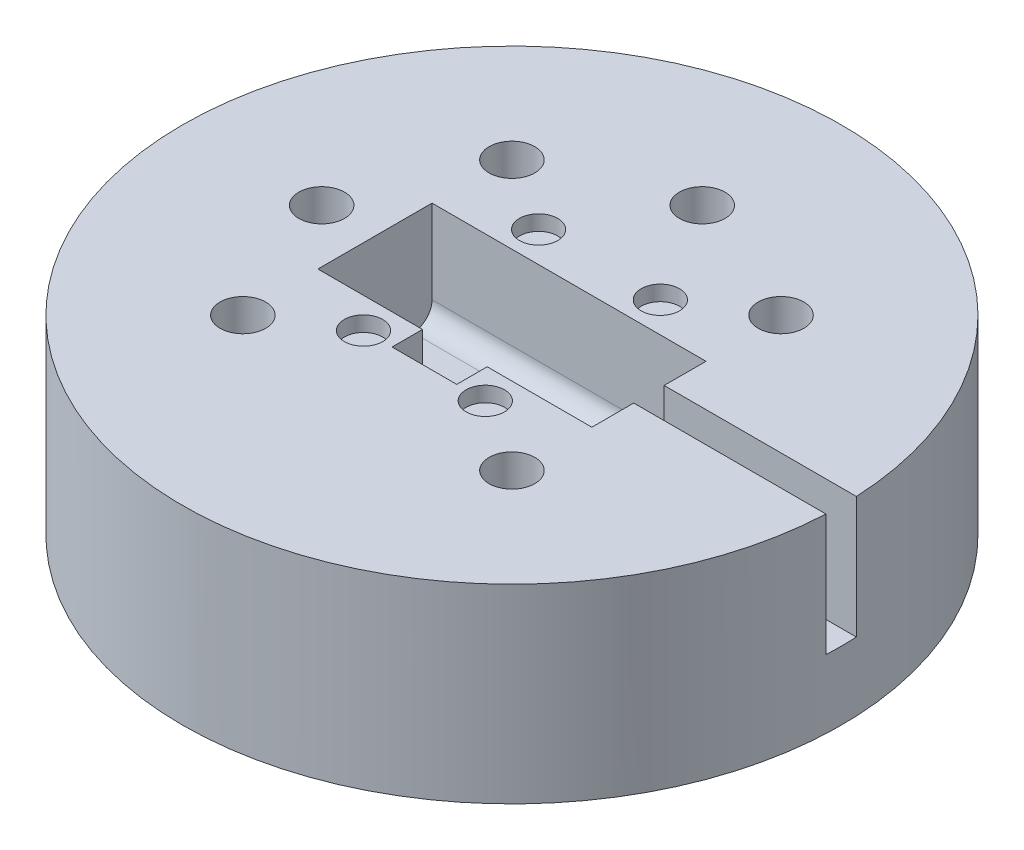
SolidWorks part; units mm, degrees
ref_plane "Front Plane" through (0, 0, 0) normal (0, 0, 1) x (1, 0, 0)
ref_plane "Top Plane" through (0, 0, 0) normal (0, 1, 0) x (1, 0, 0)
ref_plane "Right Plane" through (0, 0, 0) normal (1, 0, 0) x (0, 0, -1)
sketch "Sketch1" plane through (0, 0, 0) normal (0, 1, 0) x (1, 0, 0)
  circle A0 centre (0, 0) radius 50 construction
  circle A1 centre (0, 0) radius 86.6
extrude "Boss-Extrude1" add sketch "Sketch1" along normal blind 50
sketch "Sketch2" plane through (0, 50, 0) normal (0, 1, 0) x (1, 0, 0)
  circle A0 centre (0, 0) radius 50 construction
  circle A1 centre (0, 50) radius 6
  circle A2 centre (35.3553, 35.3553) radius 6
  circle A4 centre (35.3553, -35.3553) radius 6
  circle A6 centre (-35.3553, -35.3553) radius 6
  circle A7 centre (-50, 0) radius 6
  circle A8 centre (-35.3553, 35.3553) radius 6
  arc A9 (49.64, 5.9892) -> (49.64, -5.9892) centre (50, 0) ccw [skipped]
  arc A10 (5.9892, -49.64) -> (-5.9892, -49.64) centre (0, -50) ccw [skipped]
  point P21 (0, 0)
  dimension "D1" = 8
extrude "Cut-Extrude1" cut sketch "Sketch2" against normal blind 50
sketch "Sketch3" plane through (0, 50, 0) normal (0, 1, 0) x (1, 0, 0)
  line L0 (0, -15) -> (0, -23)
  line L1 (-36, -15) -> (36, -15)
  line L2 (-36, -15) -> (-36, 15)
  line L3 (-36, 15) -> (36, 15)
  line L4 (36, -15) -> (36, 15)
  line L5 (-36, -15) -> (36, 15) construction
  line L6 (-36, 15) -> (36, -15) construction
  line L7 (0, -23) -> (8.5, -23)
  line L8 (8.5, -23) -> (8.5, -15)
  line L9 (0, -23) -> (-8.5, -23)
  line L10 (-8.5, -23) -> (-8.5, -15)
  point P0 (0, 0)
  dimension "D1" = 8
  dimension "D2" = 8.5
  dimension "D3" = 72
  dimension "D4" = 30
extrude "Cut-Extrude2" cut sketch "Sketch3" against normal blind 27 contours L7 L8 L1 L0 | L10 L9 L0 L1 | L1 L4 L3 L2
fillet "Fillet1" radius 5 1 edges at (0, 23, -15)
fillet "Fillet2" radius 5 2 edges at (22.25, 23, 15) (-22.25, 23, 15)
sketch "Sketch4" plane through (0, 50, 0) normal (0, 1, 0) x (1, 0, 0)
  line L3 (18.5076, 4) -> (86.5076, 4)
  line L4 (18.5076, -4) -> (86.5076, -4)
  circle A1 centre (18.5076, 0) radius 4
  circle A2 centre (0, 0) radius 86.6 construction
  arc A3 (86.5076, 4) -> (86.5076, -4) centre (86.5076, 0) cw
  point P9 (20.1173, 0)
  line M8 (36, 15) -> (36, -15)
  circle M18 centre (0, 0) radius 86.6
  dimension "D1" = 8
  dimension "D2" = 68
extrude "Cut-Extrude3" cut sketch "Sketch4" against normal blind 32 contours L4 L3 M8 M18 | A1 L4 L3 M8 | A1 | A3 M18
sketch "Sketch5" plane through (0, 50, 0) normal (0, 1, 0) x (1, 0, 0)
  line L0 (-36, -15) -> (-36, -23) construction
  line L1 (-36, -23) -> (36, -23) construction
  line L2 (36, -23) -> (36, -15) construction
  line L3 (-36, -15) -> (36, -15) construction
  line L4 (-36, 15) -> (-36, 23) construction
  line L5 (-36, 23) -> (36, 23) construction
  line L6 (36, 23) -> (36, 15) construction
  line L7 (36, 15) -> (-36, 15) construction
  line L8 (-16, 23) -> (-16, 15) construction
  line L9 (16, 23) -> (16, 15) construction
  line L10 (-16, -15) -> (-16, -23) construction
  line L11 (16, -15) -> (16, -23) construction
  circle A0 centre (-16, -23) radius 5.043
  circle A1 centre (16, -23) radius 5.043
  circle A2 centre (16, 23) radius 5.043
  circle A3 centre (-16, 23) radius 5.043
  dimension "D1" = 8
  dimension "D2" = 8
  dimension "D3" = 20
  dimension "D4" = 20
  dimension "D5" = 20
  dimension "D6" = 20
extrude "Cut-Extrude4" cut sketch "Sketch5" against normal blind 4
